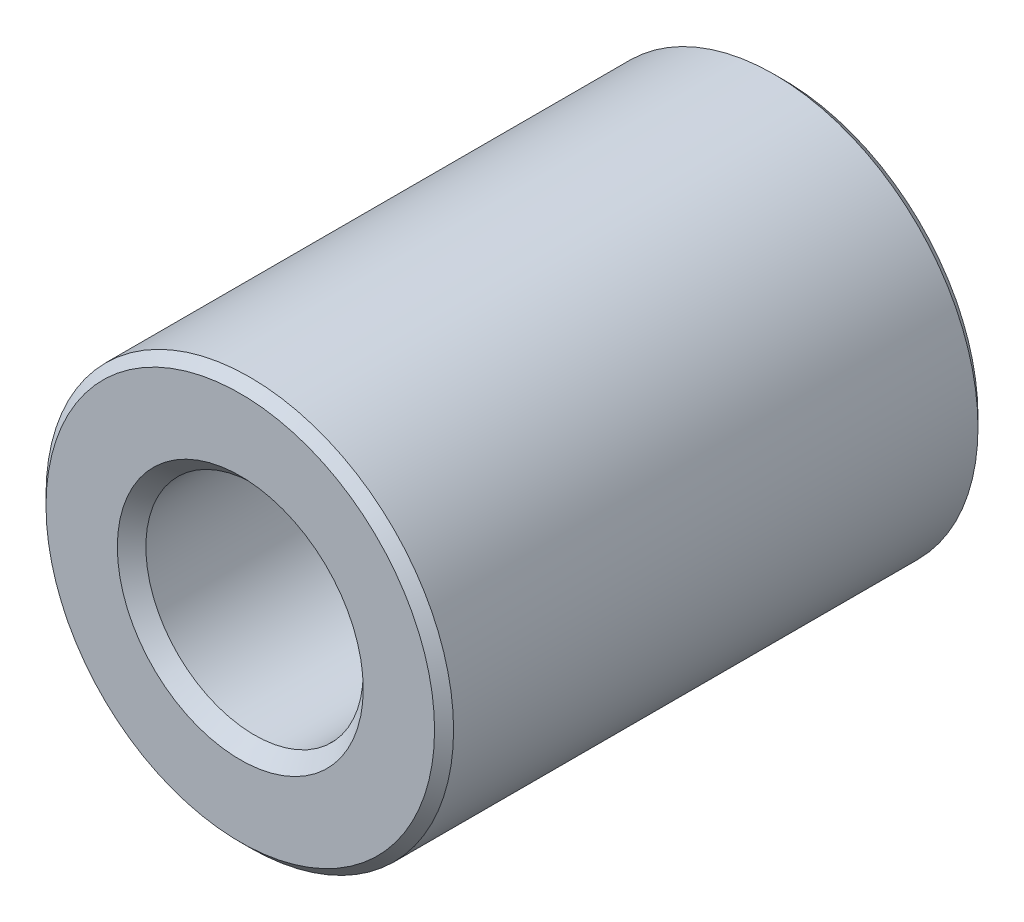
SolidWorks part; units mm, degrees
material "6061-T6 (SS)"
ref_plane "Front Plane" through (0, 0, 0) normal (0, 0, 1) x (1, 0, 0)
ref_plane "Top Plane" through (0, 0, 0) normal (0, 1, 0) x (1, 0, 0)
ref_plane "Right Plane" through (0, 0, 0) normal (1, 0, 0) x (0, 0, -1)
sketch "Sketch1" plane through (0, 0, 0) normal (0, 0, 1) x (1, 0, 0)
  circle A0 centre (0, 0) radius 3 construction
  circle A1 centre (0, 0) radius 1.6 construction
  point P4 (0, 3)
  dimension "ID" = 3.2
  dimension "OD" = 6
sketch "Sketch2" plane through (0, 0, 0) normal (1, 0, 0) x (0, 0, -1)
  line L0 (-4, 3) -> (4, 3) construction
  dimension "Length" = 8
sketch "Sketch3" plane through (0, 0, 0) normal (0, 0, 1) x (1, 0, 0)
  circle A0 centre (0, 0) radius 1.6 construction
  circle A1 centre (0, 0) radius 3 construction
  circle A2 centre (0, 0) radius 1.6
  circle A3 centre (0, 0) radius 3
extrude "Boss-Extrude1" add sketch "Sketch3" against normal up to vertex (4 mm away) and the other way up to vertex (4 mm away) up to point (0, 3, -4) other way up to point (0, 3, 4)
chamfer "Chamfer1" distance 0.14 angle 45 2 edges at (3, 0, 4) (3, 0, -4)
chamfer "Chamfer2" distance 0.21 angle 45 2 edges at (1.6, 0, 4) (1.6, 0, -4)
equation "\"D1@Chamfer1\"=(\"OD@Sketch1\"-\"ID@Sketch1\")*0.05"
equation "\"D1@Chamfer2\"=(\"OD@Sketch1\"-\"ID@Sketch1\")*0.075"
